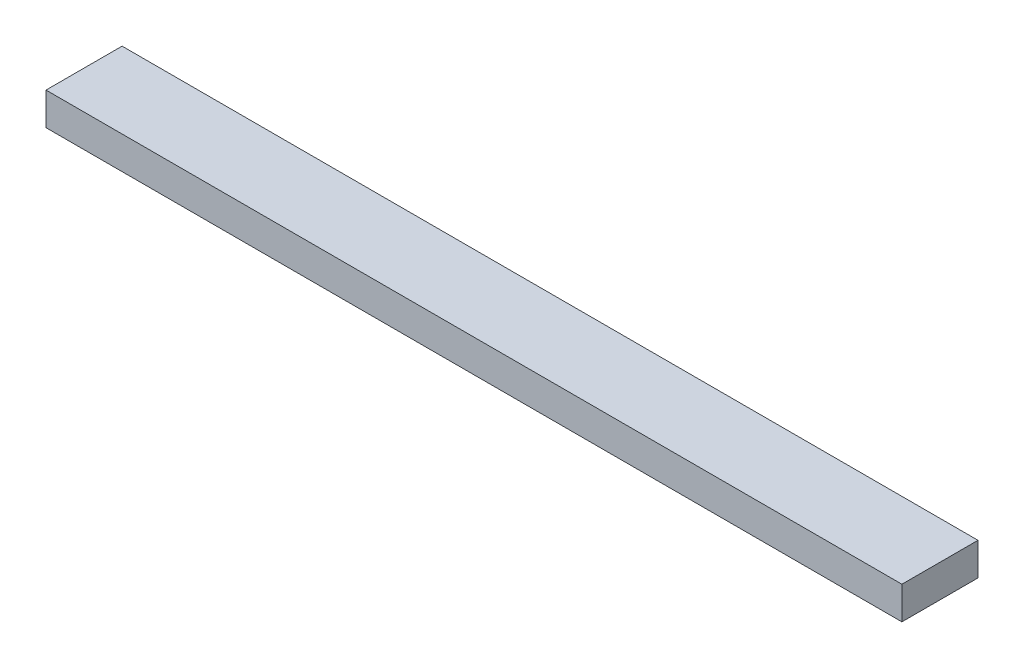
SolidWorks part; units mm, degrees
material "Pine"
ref_plane "Front Plane" through (0, 0, 0) normal (0, 0, 1) x (1, 0, 0)
ref_plane "Top Plane" through (0, 0, 0) normal (0, 1, 0) x (1, 0, 0)
ref_plane "Right Plane" through (0, 0, 0) normal (1, 0, 0) x (0, 0, -1)
sketch "Sketch1" plane through (0, 0, 0) normal (0, 1, 0) x (1, 0, 0)
  line L1 (0, 0) -> (1000, 0)
  line L2 (0, 0) -> (0, 88.9)
  line L3 (0, 88.9) -> (1000, 88.9)
  line L4 (1000, 0) -> (1000, 88.9)
  dimension "D1" = 1000
  dimension "D2" = 88.9
extrude "Boss-Extrude1" add sketch "Sketch1" along normal blind 38.1
